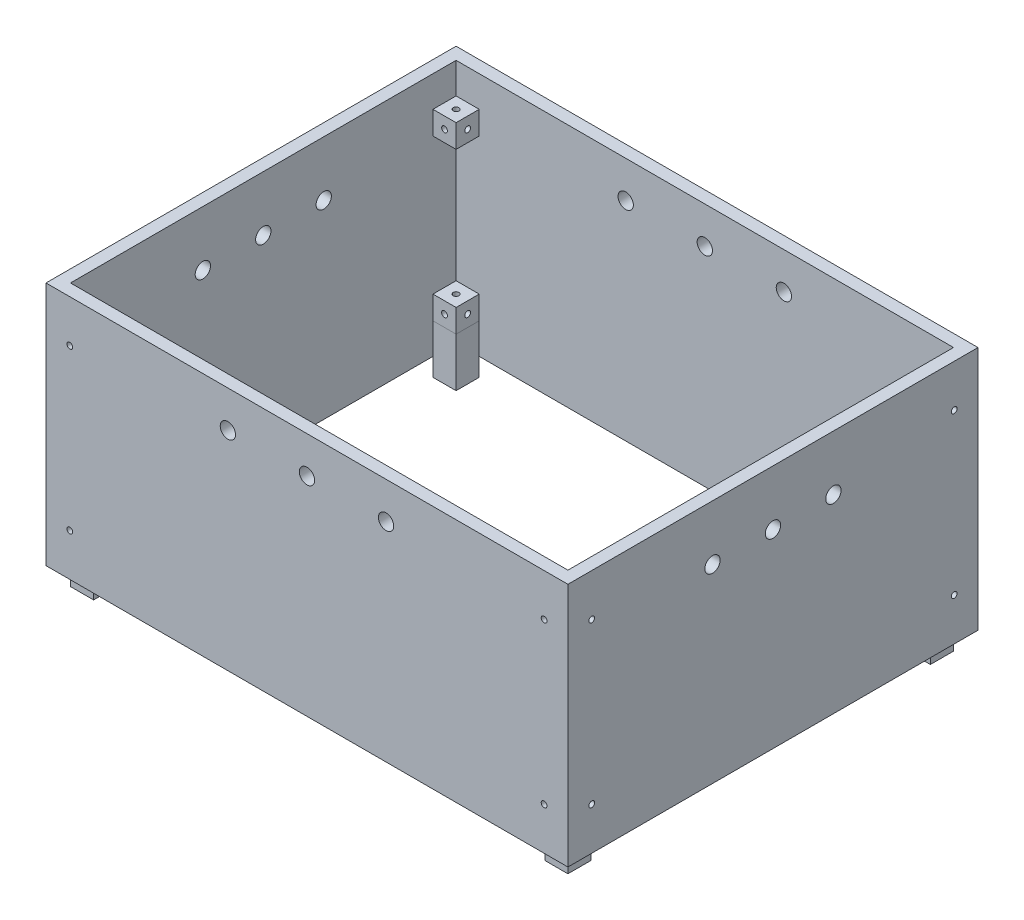
SolidWorks part; units mm, degrees
ref_plane "Front Plane" through (0, 0, 0) normal (0, 0, 1) x (1, 0, 0)
ref_plane "Top Plane" through (0, 0, 0) normal (0, 1, 0) x (1, 0, 0)
ref_plane "Right Plane" through (0, 0, 0) normal (1, 0, 0) x (0, 0, -1)
sketch "Sketch1" plane through (0, 0, 0) normal (0, 1, 0) x (1, 0, 0)
  line L1 (0, 0) -> (270.7, 0)
  line L2 (0, 0) -> (0, 212.7)
  line L3 (0, 212.7) -> (270.7, 212.7)
  line L4 (270.7, 0) -> (270.7, 212.7)
  line L5 (6.35, 6.35) -> (264.35, 6.35)
  line L6 (6.35, 6.35) -> (6.35, 206.35)
  line L7 (6.35, 206.35) -> (264.35, 206.35)
  line L8 (264.35, 6.35) -> (264.35, 206.35)
  dimension "D3" = 6.35
  dimension "D4" = 6.35
  dimension "D5" = 6.35
  dimension "D6" = 6.35
  dimension "D1" = 258
  dimension "D2" = 200
extrude "Walls" add sketch "Sketch1" along normal blind 127
sketch "Sketch2" plane through (0, 0, 0) normal (0, 0, 1) x (1, 0, 0)
  line L0 (0, 127) -> (270.7, 127) construction
  line L1 (135.35, 127) -> (135.35, 107.95) construction
  line L2 (94.33, 127) -> (94.33, 107.95) construction
  line L3 (0, 127) -> (0, 0) construction
  line L4 (176.3667, 127) -> (176.3667, 107.95) construction
  line L5 (270.7, 127) -> (270.7, 0) construction
  circle A0 centre (135.35, 107.95) radius 3.9687
  circle A1 centre (94.33, 107.95) radius 3.9687
  circle A2 centre (176.3667, 107.95) radius 3.9687
  dimension "D2" = 7.9375
  dimension "D4" = 7.9375
  dimension "D7" = 7.9375
  dimension "D1" = 19.05
  dimension "D3" = 94.33
  dimension "D5" = 19.05
  dimension "D6" = 94.3333
  dimension "D8" = 19.05
extrude "RodHolesHeight" cut sketch "Sketch2" against normal through all
sketch "Sketch4" plane through (0, 0, 0) normal (-1, 0, 0) x (0, 0, 1)
  line L0 (-106.35, 127) -> (-106.35, 98.425) construction
  line L1 (-212.7, 127) -> (0, 127) construction
  line L2 (-137.7, 127) -> (-137.7, 98.425) construction
  line L3 (-75, 127) -> (-75, 98.425) construction
  line L4 (-212.7, 127) -> (-212.7, 0) construction
  line L5 (0, 127) -> (0, 0) construction
  circle A0 centre (-106.35, 98.425) radius 3.9687
  circle A1 centre (-137.7, 98.425) radius 3.9687
  circle A2 centre (-75, 98.425) radius 3.9688
  dimension "D2" = 7.9375
  dimension "D5" = 7.9375
  dimension "D6" = 7.9375
  dimension "D1" = 28.575
  dimension "D3" = 75
  dimension "D4" = 75
  dimension "D7" = 28.575
  dimension "D8" = 28.575
extrude "RodHolesWidth" cut sketch "Sketch4" against normal through all contours A1 | A0 | A2
sketch "Sketch3" plane through (0, 0, -6.35) normal (0, 0, -1) x (-1, 0, 0)
  line L14 (-264.35, 111) -> (-252.35, 111)
  line L15 (-264.35, 111) -> (-264.35, 99)
  line L16 (-264.35, 99) -> (-252.35, 99)
  line L17 (-264.35, 0) -> (-6.35, 0)
  line L18 (-6.35, 0) -> (-6.35, 127)
  line L19 (-6.35, 127) -> (-264.35, 127)
  line L20 (-264.35, 127) -> (-264.35, 0)
  line L21 (-264.35, 0) -> (-6.35, 0)
  line L22 (-6.35, 0) -> (-6.35, 127)
  line L23 (-6.35, 127) -> (-264.35, 127)
  line L24 (-264.35, 127) -> (-264.35, 0)
  line L25 (-252.35, 111) -> (-252.35, 99)
  line L26 (-6.35, 111) -> (-18.35, 111)
  line L27 (-6.35, 111) -> (-6.35, 99)
  line L28 (-6.35, 99) -> (-18.35, 99)
  line L29 (-18.35, 111) -> (-18.35, 99)
  line L30 (-264.35, 28) -> (-252.35, 28)
  line L31 (-264.35, 28) -> (-264.35, 16)
  line L32 (-264.35, 16) -> (-252.35, 16)
  line L33 (-252.35, 28) -> (-252.35, 16)
  line L34 (-6.35, 28) -> (-18.35, 28)
  line L35 (-6.35, 28) -> (-6.35, 16)
  line L36 (-6.35, 16) -> (-18.35, 16)
  line L37 (-18.35, 28) -> (-18.35, 16)
  point P20 (-258.35, 16)
  line M35 (-264.35, 127) -> (-264.35, 0)
  dimension "D2" = 12
  dimension "D3" = 16
  dimension "D4" = 16
extrude "ModdingCube" add sketch "Sketch3" along normal blind 12 contours L25 L14 L16 M35 | L33 L30 L24 L32 | L34 L37 L36 L22 | L26 L29 L28 L22
sketch "Sketch11" plane through (0, 0, -18.35) normal (0, 0, -1) x (-1, 0, 0)
  line L0 (-258.35, 111) -> (-258.35, 105) construction
  line L1 (-264.35, 111) -> (-252.35, 111) construction
  line L2 (-258.35, 105) -> (-252.35, 105) construction
  line L3 (-252.35, 111) -> (-252.35, 99) construction
  line L4 (-12.35, 111) -> (-12.35, 105) construction
  line L5 (-6.35, 111) -> (-18.35, 111) construction
  line L6 (-12.35, 105) -> (-18.35, 105) construction
  line L7 (-18.35, 111) -> (-18.35, 99) construction
  line L8 (-12.35, 28) -> (-12.35, 22) construction
  line L9 (-6.35, 28) -> (-18.35, 28) construction
  line L10 (-12.35, 22) -> (-18.35, 22) construction
  line L11 (-18.35, 28) -> (-18.35, 16) construction
  line L12 (-258.35, 28) -> (-258.35, 22) construction
  line L13 (-264.35, 28) -> (-252.35, 28) construction
  line L14 (-258.35, 22) -> (-252.35, 22) construction
  line L15 (-252.35, 28) -> (-252.35, 16) construction
  line L16 (-252.35, 22) -> (-258.35, 22) construction
  circle A1 centre (-258.35, 105) radius 1.5
  circle A2 centre (-258.35, 22) radius 1.5
  circle A3 centre (-12.35, 105) radius 1.5
  circle A4 centre (-12.35, 22) radius 1.5
  dimension "D1" = 3
extrude "Cut-Extrude1" cut sketch "Sketch11" against normal through all both and the other way through all contours A2 | A1 | A3 | A4
sketch "Sketch17" plane through (0, 28, 0) normal (0, 1, 0) x (1, 0, 0)
  line L0 (12.35, 18.35) -> (12.35, 12.35) construction
  line L1 (6.35, 18.35) -> (18.35, 18.35) construction
  line L2 (12.35, 12.35) -> (18.35, 12.35) construction
  line L3 (18.35, 18.35) -> (18.35, 6.35) construction
  line L4 (258.35, 18.35) -> (258.35, 12.35) construction
  line L5 (264.35, 18.35) -> (252.35, 18.35) construction
  line L6 (258.35, 12.35) -> (252.35, 12.35) construction
  line L7 (252.35, 18.35) -> (252.35, 6.35) construction
  circle A0 centre (12.35, 12.35) radius 1.5
  circle A1 centre (258.35, 12.35) radius 1.5
  dimension "D1" = 3
  dimension "D2" = 3
extrude "Cut-Extrude4" cut sketch "Sketch17" against normal through all both and the other way through all
sketch "Sketch15" plane through (252.35, 0, 0) normal (-1, 0, 0) x (0, 0, 1)
  line L0 (-12.35, 111) -> (-12.35, 105) construction
  line L1 (-18.35, 111) -> (-6.35, 111) construction
  line L2 (-12.35, 105) -> (-18.35, 105) construction
  line L3 (-18.35, 111) -> (-18.35, 99) construction
  line L5 (-12.35, 28) -> (-12.35, 22) construction
  line L6 (-18.35, 28) -> (-6.35, 28) construction
  line L7 (-12.35, 22) -> (-18.35, 22) construction
  line L8 (-18.35, 28) -> (-18.35, 16) construction
  circle A0 centre (-12.35, 105) radius 1.5
  circle A1 centre (-12.35, 22) radius 1.5
  dimension "D1" = 3
  dimension "D2" = 3
extrude "Cut-Extrude2" cut sketch "Sketch15" against normal through all both and the other way through all
ref_plane "Plane2" through (0, 0, -106.35) normal (0, 0, -1) x (-1, 0, 0)
mirror "Mirror6" about plane through (0, 0, -106.35) normal (0, 0, -1) of "Cut-Extrude2", "Cut-Extrude4", "Cut-Extrude1", "ModdingCube"
sketch "Sketch18" plane through (0, 16, 0) normal (0, -1, 0) x (1, 0, 0)
  line L1 (6.35, -6.35) -> (18.35, -6.35)
  line L2 (6.35, -6.35) -> (6.35, -18.35)
  line L3 (6.35, -18.35) -> (18.35, -18.35)
  line L4 (18.35, -6.35) -> (18.35, -18.35)
  line L5 (6.35, -206.35) -> (18.35, -206.35)
  line L6 (6.35, -206.35) -> (6.35, -194.35)
  line L7 (6.35, -194.35) -> (18.35, -194.35)
  line L8 (18.35, -206.35) -> (18.35, -194.35)
  line L9 (264.35, -206.35) -> (252.35, -206.35)
  line L10 (264.35, -206.35) -> (264.35, -194.35)
  line L11 (264.35, -194.35) -> (252.35, -194.35)
  line L12 (252.35, -206.35) -> (252.35, -194.35)
  line L13 (264.35, -6.35) -> (252.35, -6.35)
  line L14 (264.35, -6.35) -> (264.35, -18.35)
  line L15 (264.35, -18.35) -> (252.35, -18.35)
  line L16 (252.35, -6.35) -> (252.35, -18.35)
extrude "Pegs" add sketch "Sketch18" along normal blind 25.4 separate body
equation "\"Length\"= 283mm"
equation "\"Width\"= 225mm"
equation "\"WallThickness\"= 12.5mm"
equation "\"UpperWaterJacketThickness\"= 28mm"
equation "\"SpacerHeight\"= 80.2mm"
equation "\"SpacerCornerWidth\"= 10mm"
equation "\"SpacerCornerHeight\"= 60.16mm"
equation "\"SpacerPegDiameter\"= 10mm"
equation "\"SpacerPegHeight\"= 10mm"
equation "\"TubingShort\"= 110mm"
equation "\"TubingLong\"= 175mm"
equation "\"PlateLength\"= 252mm"
equation "\"PlateWidth\"= 190mm"
equation "\"PlateHoleDiameter\"= 5.9mm"
equation "\"PlateHoleBottom\"= 2mm"
equation "\"PlateHoleSide\"= 1.55mm"
equation "\"PlateHoleSpacing\"= 3.1mm"
equation "\"PlateThickness\"= 1.55mm"
equation "\"ReservoirBottom\"= 12.5mm"
equation "\"ReservoirSupportWidth\"= 12mm"
equation "\"ReservoirSupportHeight\"= 15.1mm"
equation "\"ReservoirSupportPlacementHeight\"= 50mm"
equation "\"ReservoirHoleDiameter\"= 12.7mm"
equation "\"ReservoirHoleRight\"= 25mm"
equation "\"ReservoirHoleTop\"= \"ReservoirSupportPlacementHeight\""
equation "\"ReservoirHeight\"= 90mm"
equation "\"ReservoirPortBottom\"= 4mm"
equation "\"ReservoirPortTop\"= 10mm"
equation "\"ReservoirPortWidth\"= 101mm"
equation "\"D3@Sketch1\"=\"CustomSpacerWallThickness\""
equation "\"D4@Sketch1\"=\"CustomSpacerWallThickness\""
equation "\"CustomSpacerWallThickness\" = 6.35mm"
equation "\"D5@Sketch1\"=\"CustomSpacerWallThickness\""
equation "\"D6@Sketch1\"=\"CustomSpacerWallThickness\""
equation "\"CustomSpacerHeight\" = 5in"
equation "\"D1@Walls\" = \"CustomSpacerHeight\""
equation "\"CustomSpacerRodHoleHeight\" = .75in"
equation "\"CustomSpacerRodHoleDiameter\" = .3125in"
equation "\"D4@Sketch2\"=\"CustomSpacerRodHoleDiameter\""
equation "\"D5@Sketch2\"=\"CustomSpacerRodHoleHeight\""
equation "\"D2@Sketch2\"=\"CustomSpacerRodHoleDiameter\""
equation "\"D6@Sketch2\"=\"Length\"/3"
equation "\"D7@Sketch2\"=\"CustomSpacerRodHoleDiameter\""
equation "\"D8@Sketch2\"=\"CustomSpacerRodHoleHeight\""
equation "\"ScrewBlockSide\"= 12mm"
equation "\"D2@Sketch3\"=\"ScrewBlockSide\""
equation "\"ScrewBlockUpperHeight\" = 16mm"
equation "\"D3@Sketch3\"=\"ScrewBlockUpperHeight\""
equation "\"ScrewBlockLowerHeight\" = 16mm"
equation "\"D4@Sketch3\"=\"ScrewBlockLowerHeight\""
equation "\"D1@ModdingCube\" = \"ScrewBlockSide\""
equation "\"InternalLength\" = \"Length\" - ( 2 * \"WallThickness\" )"
equation "\"D1@Sketch1\"=\"InternalLength\""
equation "\"InternalWidth\"= \"Width\" - ( 2 * \"WallThickness\" )"
equation "\"D2@Sketch1\"=\"InternalWidth\""
equation "\"D1@Sketch4\"=\"CustomSpacerRodHoleHeight\"+\"CustomSpacerRodHoleDiameter\"+0.0625in"
equation "\"D2@Sketch4\"=\"CustomSpacerRodHoleDiameter\""
equation "\"D3@Sketch4\"=\"Width\"/3"
equation "\"D4@Sketch4\"=\"Width\"/3"
equation "\"D5@Sketch4\"=\"CustomSpacerRodHoleDiameter\""
equation "\"D6@Sketch4\"=\"CustomSpacerRodHoleDiameter\""
equation "\"D7@Sketch4\"=\"CustomSpacerRodHoleHeight\"+\"CustomSpacerRodHoleDiameter\"+0.0625in"
equation "\"D8@Sketch4\"=\"CustomSpacerRodHoleHeight\"+\"CustomSpacerRodHoleDiameter\"+0.0625in"
equation "\"CustomSpacerPegHeight\" = 1in"
equation "\"CustomSpacerScrewBore\"=3mm"
equation "\"D1@Sketch11\"=\"CustomSpacerScrewBore\""
equation "\"D1\" = \"ScrewBlockSide\" / 2"
equation "\"D1@Sketch15\"=\"CustomSpacerScrewBore\""
equation "\"D2@Sketch15\"=\"CustomSpacerScrewBore\""
equation "\"D2@Sketch17\"=\"CustomSpacerScrewBore\""
equation "\"D1@Pegs\" = \"CustomSpacerPegHeight\""
equation "\"CustomSpacerScrewDepth\"=10mm"
